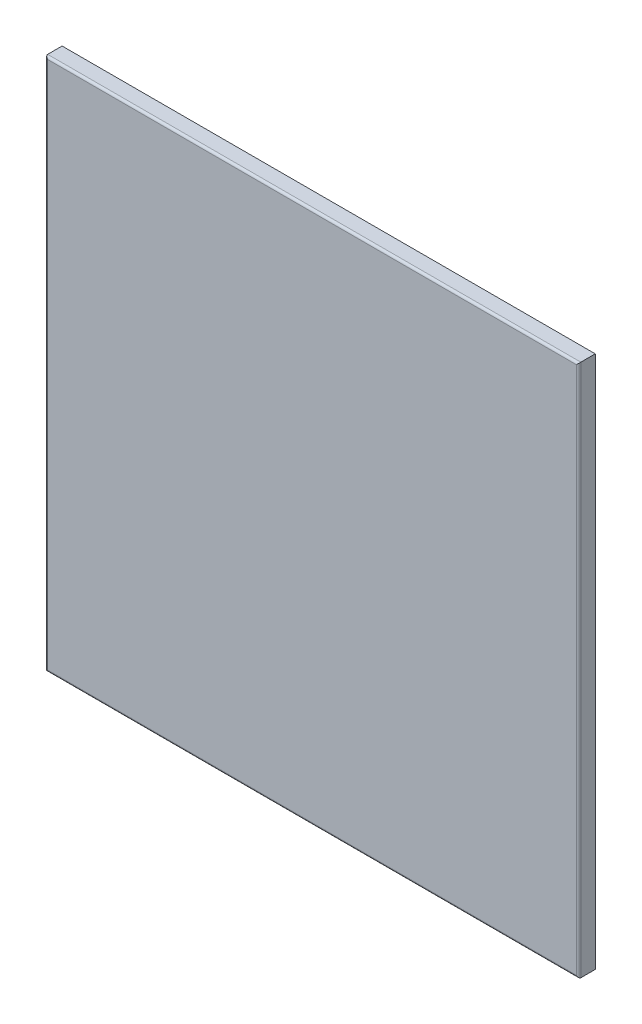
SolidWorks part; units mm, degrees
ref_plane "Front Plane" through (0, 0, 0) normal (0, 0, 1) x (1, 0, 0)
ref_plane "Top Plane" through (0, 0, 0) normal (0, 1, 0) x (1, 0, 0)
ref_plane "Right Plane" through (0, 0, 0) normal (1, 0, 0) x (0, 0, -1)
sketch "Sketch1" plane through (0, 0, 0) normal (0, 0, 1) x (1, 0, 0)
  line L1 (-304.8, 304.8) -> (304.8, 304.8)
  line L2 (-304.8, 304.8) -> (-304.8, -304.8)
  line L3 (-304.8, -304.8) -> (304.8, -304.8)
  line L4 (304.8, 304.8) -> (304.8, -304.8)
  line L5 (-304.8, 304.8) -> (304.8, -304.8) construction
  line L6 (-304.8, -304.8) -> (304.8, 304.8) construction
  point P0 (0, 0)
  dimension "D1" = 609.6
  dimension "D2" = 609.6
extrude "Boss-Extrude1" add sketch "Sketch1" along normal blind 2.54
sketch "Sketch2" plane through (0, 0, 2.54) normal (0, 0, 1) x (1, 0, 0)
  line L0 (302.26, 302.26) -> (-302.26, 302.26)
  line L1 (-302.26, 302.26) -> (-302.26, -302.26)
  line L2 (-302.26, -302.26) -> (302.26, -302.26)
  line L3 (302.26, -302.26) -> (302.26, 302.26)
  line L4 (304.8, -304.8) -> (304.8, 304.8)
  line L5 (304.8, 304.8) -> (-304.8, 304.8)
  line L6 (-304.8, 304.8) -> (-304.8, -304.8)
  line L7 (-304.8, -304.8) -> (304.8, -304.8)
  line L8 (304.8, -304.8) -> (304.8, 304.8)
  line L9 (304.8, 304.8) -> (-304.8, 304.8)
  line L10 (-304.8, 304.8) -> (-304.8, -304.8)
  line L11 (-304.8, -304.8) -> (304.8, -304.8)
  dimension "D1" = 0
  dimension "D2" = 2.54
extrude "Boss-Extrude2" add sketch "Sketch2" against normal blind 19.05
fillet "Fillet1" radius 2.54 4 edges at (0, -304.8, 2.54) (-304.8, 0, 2.54) (0, 304.8, 2.54) (304.8, 0, 2.54)
